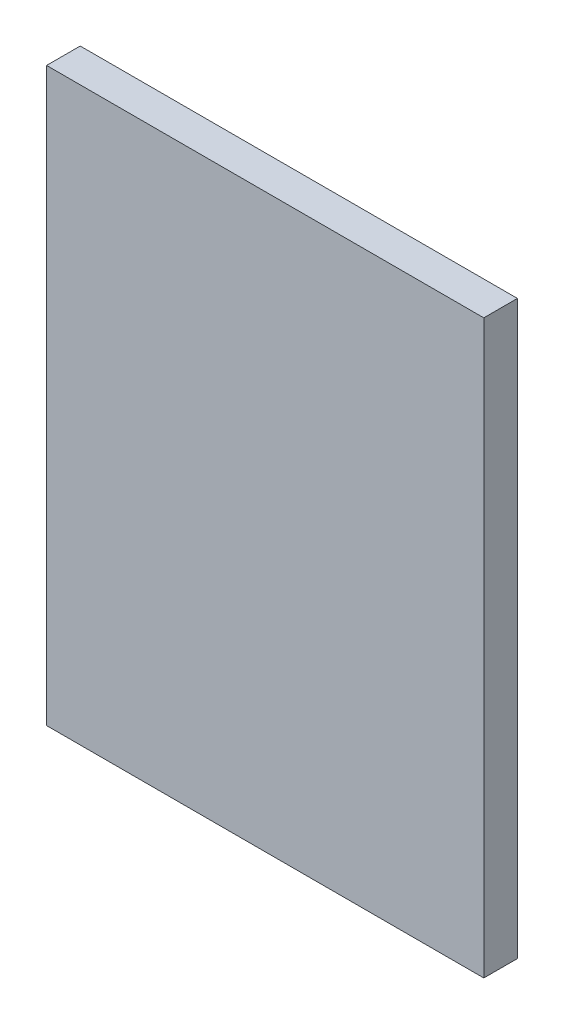
SolidWorks part; units mm, degrees
ref_plane "Alzado" through (0, 0, 0) normal (0, 0, 1) x (1, 0, 0)
ref_plane "Planta" through (0, 0, 0) normal (0, 1, 0) x (1, 0, 0)
ref_plane "Vista lateral" through (0, 0, 0) normal (1, 0, 0) x (0, 0, -1)
sketch "Croquis1" plane through (0, 0, 0) normal (0, 0, 1) x (1, 0, 0)
  line L1 (13, -17) -> (-13, -17)
  line L2 (13, -17) -> (13, 17)
  line L3 (13, 17) -> (-13, 17)
  line L4 (-13, -17) -> (-13, 17)
  line L5 (13, -17) -> (-13, 17) construction
  line L6 (13, 17) -> (-13, -17) construction
  point P0 (0, 0)
  dimension "D1" = 26
  dimension "D2" = 34
extrude "Saliente-Extruir1" add sketch "Croquis1" along normal blind 2
